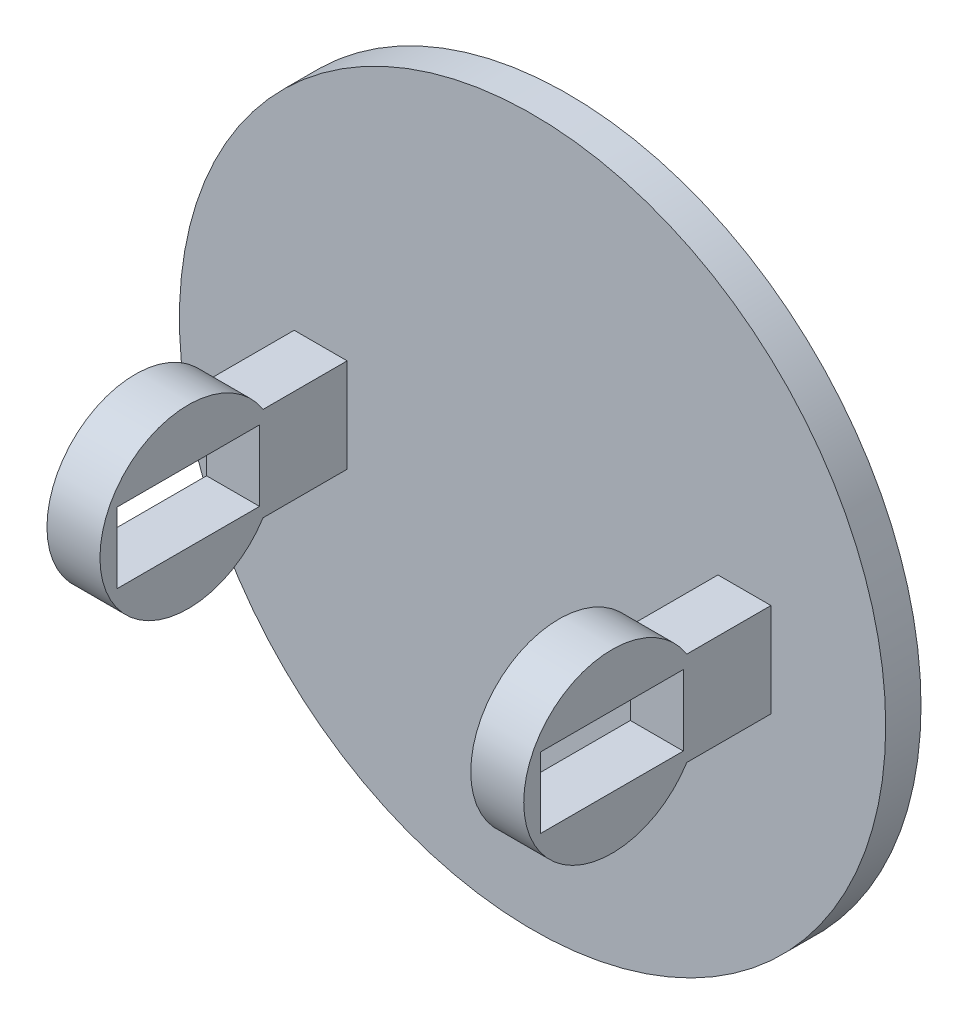
SolidWorks part; units mm, degrees
ref_plane "Front Plane" through (0, 0, 0) normal (0, 0, 1) x (1, 0, 0)
ref_plane "Top Plane" through (0, 0, 0) normal (0, 1, 0) x (1, 0, 0)
ref_plane "Right Plane" through (0, 0, 0) normal (1, 0, 0) x (0, 0, -1)
sketch "Sketch1" plane through (0, 0, 0) normal (0, 0, 1) x (1, 0, 0)
  circle A0 centre (0, 0) radius 100
  dimension "D1" = 200
extrude "Boss-Extrude1" add sketch "Sketch1" against normal blind 10
sketch "Sketch2" plane through (0, 0, -10) normal (0, 0, -1) x (-1, 0, 0)
  circle A0 centre (0, 0) radius 25
  dimension "D1" = 50
extrude "Boss-Extrude2" add sketch "Sketch2" along normal blind 25
sketch "Sketch3" plane through (0, 0, 0) normal (0, 0, 1) x (1, 0, 0)
  line L0 (0, 61.4799) -> (0, -63.6488) construction
  line L1 (-83.7528, 0) -> (66.7353, 0) construction
  line L2 (-60, 61.4799) -> (-60, -63.6488) construction
  line L4 (-67.5, 40) -> (-52.5, 40)
  line L5 (-67.5, 40) -> (-67.5, -40)
  line L6 (-67.5, -40) -> (-52.5, -40)
  line L7 (-52.5, 40) -> (-52.5, -40)
  line L8 (-67.5, 40) -> (-52.5, -40) construction
  line L9 (-67.5, -40) -> (-52.5, 40) construction
  point P7 (-60, 0)
  dimension "D2" = 80
  dimension "D3" = 15
  dimension "D1" = 60
extrude "Boss-Extrude3" add sketch "Sketch3" along normal blind 70
sketch "Sketch5" plane through (-67.5, 0, 0) normal (-1, 0, 0) x (0, 0, 1)
  line L0 (62.2762, 0) -> (-21.0201, 0) construction
  line L1 (70, 40) -> (70, -40) construction
  line L4 (0, 40) -> (0, -40) construction
  line L8 (70, 40) -> (70, -40)
  line L9 (70, 40) -> (0, 40) construction
  line L10 (70, 40) -> (0, 40)
  line L11 (0, 40) -> (0, -40)
  line L12 (70, -40) -> (0, -40) construction
  line L13 (70, -40) -> (0, -40)
  line L14 (23.824, 13.2882) -> (0, 13.2882)
  line L16 (23.824, -13.2882) -> (0, -13.2882)
  line L18 (0, 13.2882) -> (0, -13.2882)
  arc A0 (23.824, -13.2882) -> (23.824, 13.2882) centre (45, 0) ccw
  point P7 (62.2762, 10)
  point P8 (-21.0201, 10)
  dimension "D1" = 50
extrude "Cut-Extrude1" cut sketch "Sketch5" against normal blind 40
mirror "Mirror2" about plane through (0, 0, 0) normal (1, 0, 0) of "Cut-Extrude1", "Boss-Extrude3"
sketch "Sketch7" plane through (-67.5, 0, 0) normal (-1, 0, 0) x (0, 0, 1)
  line L1 (65.1909, 10) -> (24.8091, 10)
  line L2 (65.1909, 10) -> (65.1909, -10)
  line L3 (65.1909, -10) -> (24.8091, -10)
  line L4 (24.8091, 10) -> (24.8091, -10)
  line L5 (65.1909, 10) -> (24.8091, -10) construction
  line L6 (65.1909, -10) -> (24.8091, 10) construction
  point P0 (45, 0)
  dimension "D1" = 20
extrude "Cut-Extrude2" cut sketch "Sketch7" against normal through all
